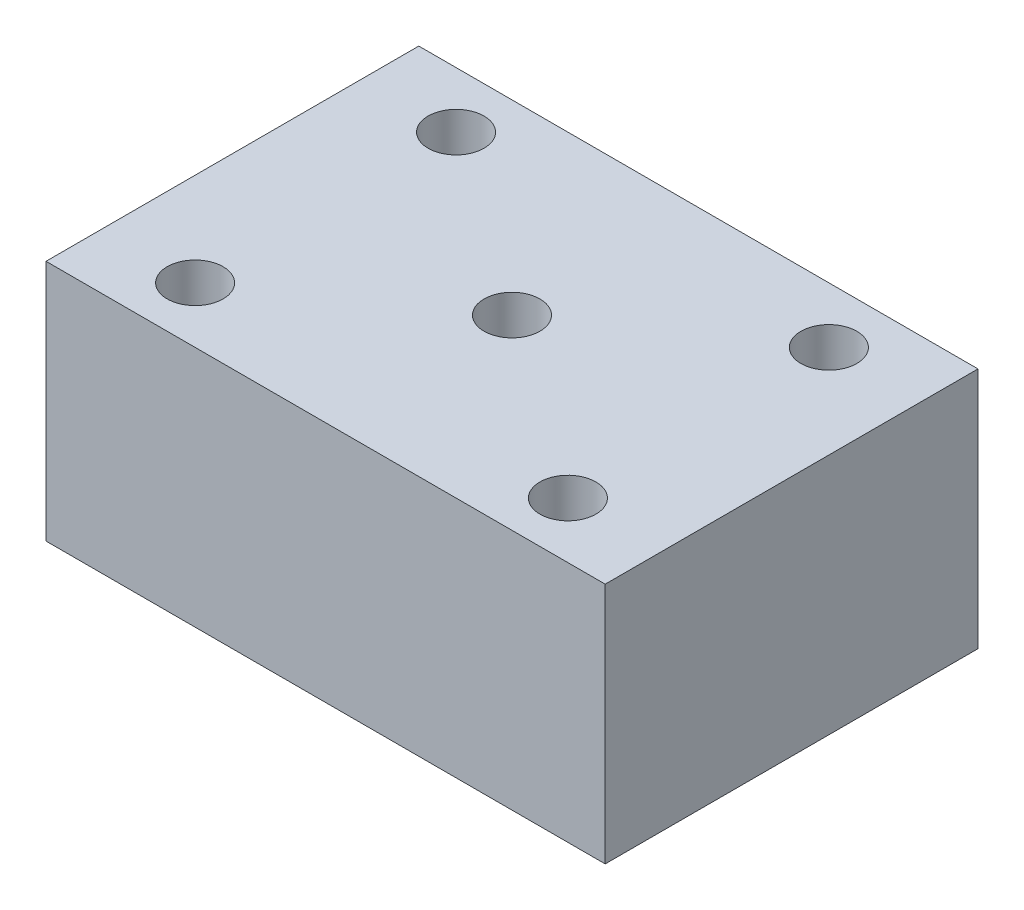
SolidWorks part; units mm, degrees
material "1060 合金"
ref_plane "前视基准面" through (0, 0, 0) normal (0, 0, 1) x (1, 0, 0)
ref_plane "上视基准面" through (0, 0, 0) normal (0, 1, 0) x (1, 0, 0)
ref_plane "右视基准面" through (0, 0, 0) normal (1, 0, 0) x (0, 0, -1)
sketch "草图1" plane through (0, 0, 0) normal (0, 1, 0) x (1, 0, 0)
  line L0 (0, -10) -> (0, 10) construction
  line L1 (-15, 10) -> (15, 10)
  line L2 (-15, 10) -> (-15, -10)
  line L3 (-15, -10) -> (15, -10)
  line L4 (15, 10) -> (15, -10)
  line L5 (-15, 0) -> (15, 0) construction
  circle A0 centre (-10, -7) radius 1.5
  circle A1 centre (10, -7) radius 1.5
  circle A2 centre (10, 7) radius 1.5
  circle A3 centre (-10, 7) radius 1.5
  circle A4 centre (0, 0) radius 1.5
  point P4 (0, -10)
  point P5 (15, 0)
  dimension "D3" = 3
  dimension "D6" = 3
  dimension "D1" = 20
  dimension "D2" = 30
  dimension "D4" = 5
  dimension "D5" = 3
extrude "凸台-拉伸1" add sketch "草图1" along normal blind 13
